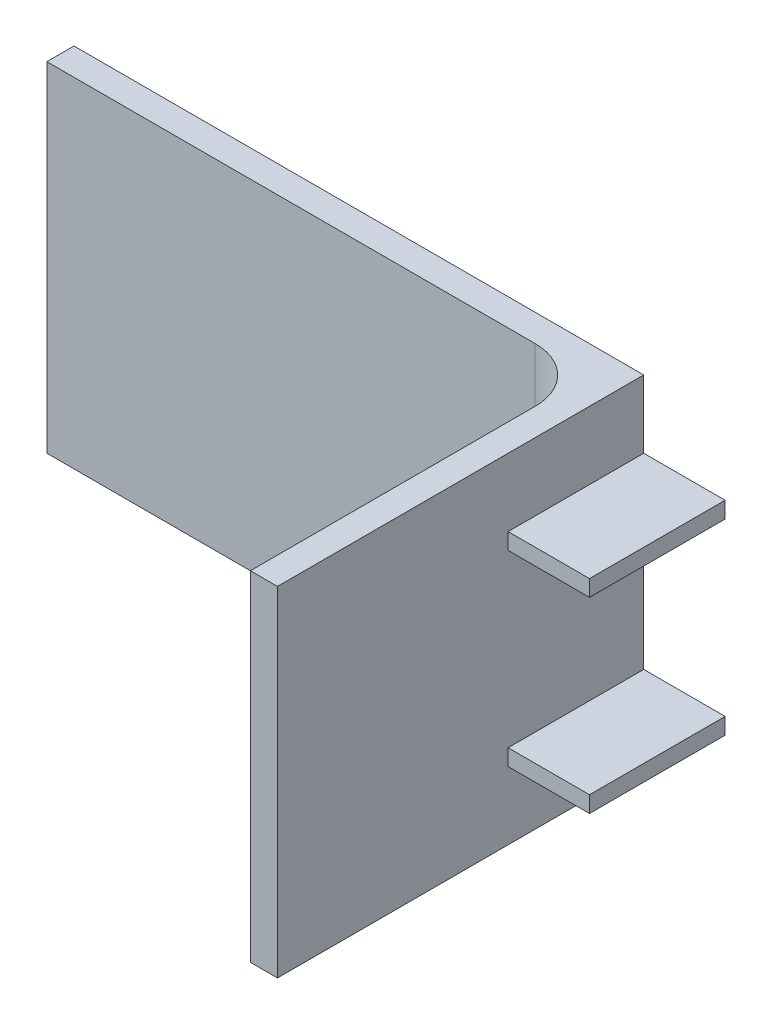
SolidWorks part; units mm, degrees
ref_plane "Front Plane" through (0, 0, 0) normal (0, 0, 1) x (1, 0, 0)
ref_plane "Top Plane" through (0, 0, 0) normal (0, 1, 0) x (1, 0, 0)
ref_plane "Right Plane" through (0, 0, 0) normal (1, 0, 0) x (0, 0, -1)
sketch "Sketch1" plane through (0, 0, 0) normal (0, 0, 1) x (1, 0, 0)
  line L1 (-42, 25) -> (0, 25)
  line L2 (-42, 25) -> (-42, 0)
  line L3 (-42, 0) -> (0, 0)
  line L4 (0, 25) -> (0, 0)
  dimension "D1" = 25
  dimension "D2" = 42
extrude "Boss-Extrude1" add sketch "Sketch1" along normal blind 2
sketch "Sketch2" plane through (0, 0, 2) normal (0, 0, 1) x (1, 0, 0)
  line L0 (-42, 0) -> (0, 0) construction
  line L1 (0, 25) -> (-2, 25)
  line L2 (0, 25) -> (0, 0)
  line L3 (0, 0) -> (-2, 0)
  line L4 (-2, 25) -> (-2, 0)
  dimension "D1" = 2
extrude "Boss-Extrude2" add sketch "Sketch2" along normal blind 25
sketch "Sketch3" plane through (0, 0, 0) normal (1, 0, 0) x (0, 0, -1)
  line L0 (-27, 25) -> (0, 25) construction
  line L1 (0, 20) -> (-10, 20)
  line L2 (0, 20) -> (0, 18.8)
  line L3 (0, 18.8) -> (-10, 18.8)
  line L4 (-10, 20) -> (-10, 18.8)
  line L5 (0, 5) -> (-10, 5)
  line L6 (0, 5) -> (0, 6.2)
  line L7 (0, 6.2) -> (-10, 6.2)
  line L8 (-10, 5) -> (-10, 6.2)
  line L9 (-27, 0) -> (0, 0) construction
  dimension "D1" = 1.2
  dimension "D2" = 10
  dimension "D3" = 1.2
  dimension "D4" = 10
  dimension "D5" = 5
  dimension "D6" = 5
extrude "Boss-Extrude3" add sketch "Sketch3" along normal blind 6
fillet "Fillet1" radius 4 1 edges
